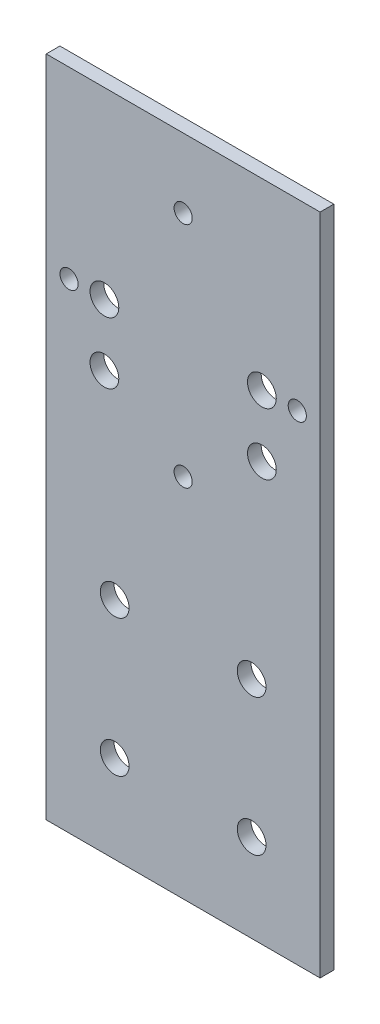
SolidWorks part; units mm, degrees
ref_plane "Front Plane" through (0, 0, 0) normal (0, 0, 1) x (1, 0, 0)
ref_plane "Top Plane" through (0, 0, 0) normal (0, 1, 0) x (1, 0, 0)
ref_plane "Right Plane" through (0, 0, 0) normal (1, 0, 0) x (0, 0, -1)
sketch "Sketch1" plane through (0, 0, 0) normal (0, 0, 1) x (1, 0, 0)
  line L1 (1820.4212, -1907.5842) -> (1740.4212, -1907.5842)
  line L2 (1820.4212, -1907.5842) -> (1820.4212, -1713.8282)
  line L3 (1820.4212, -1713.8282) -> (1740.4212, -1713.8282)
  line L4 (1740.4212, -1907.5842) -> (1740.4212, -1713.8282)
  line L5 (1764.2212, -1739.2194) -> (1755.2212, -1739.2194) construction
extrude "Boss-Extrude1" add sketch "Sketch1" along normal blind 4
hole_wizard "M8 Clearance Hole1" positions "Sketch3" profile "Sketch2" hole size "M8" standard "ISO" end condition through all
sketch "Sketch3" plane through (0, 0, 4) normal (0, 0, 1) x (1, 0, 0)
  point P2 (1757.4212, -1767.4194)
  point P4 (1803.4212, -1767.4194)
  point P6 (1803.4212, -1785.4194)
  point P8 (1757.4212, -1785.4194)
  point P10 (1800.4212, -1841.9194)
  point P12 (1760.4212, -1841.9194)
  point P16 (1800.4212, -1881.9194)
  point P18 (1760.4212, -1881.9194)
  dimension "D1" = 40
  dimension "40" = 40
sketch "Sketch2" plane through (1757.4212, -1767.4194, 4) normal (1, 0, 0) x (0, -1, 0)
  line L0 (0, 0) -> (0, 4)
  line L1 (0, 4) -> (4.2, 4)
  line L2 (4.2, 4) -> (4.2, 0)
  line L5 (4.2, 0) -> (0, 0)
  line L11 (0, -6.35) -> (0, 107.95) construction
  dimension "Thru Hole Dia." = 8.4
  dimension "Thru Hole Depth" = 4
hole_wizard "M5 Clearance Hole1" positions "Sketch5" profile "Sketch4" hole size "M5" standard "ISO" end condition through all
sketch "Sketch5" plane through (0, 0, 4) normal (0, 0, 1) x (1, 0, 0)
  point P0 (1813.7542, -1767.4194)
  point P2 (1747.0882, -1767.4194)
  point P4 (1780.4212, -1734.0864)
  point P6 (1780.4212, -1800.7524)
sketch "Sketch4" plane through (1813.7542, -1767.4194, 4) normal (1, 0, 0) x (0, -1, 0)
  line L0 (0, 0) -> (0, 4)
  line L1 (0, 4) -> (2.65, 4)
  line L2 (2.65, 4) -> (2.65, 0)
  line L5 (2.65, 0) -> (0, 0)
  line L11 (0, -6.35) -> (0, 107.95) construction
  dimension "Thru Hole Dia." = 5.3
  dimension "Thru Hole Depth" = 4
